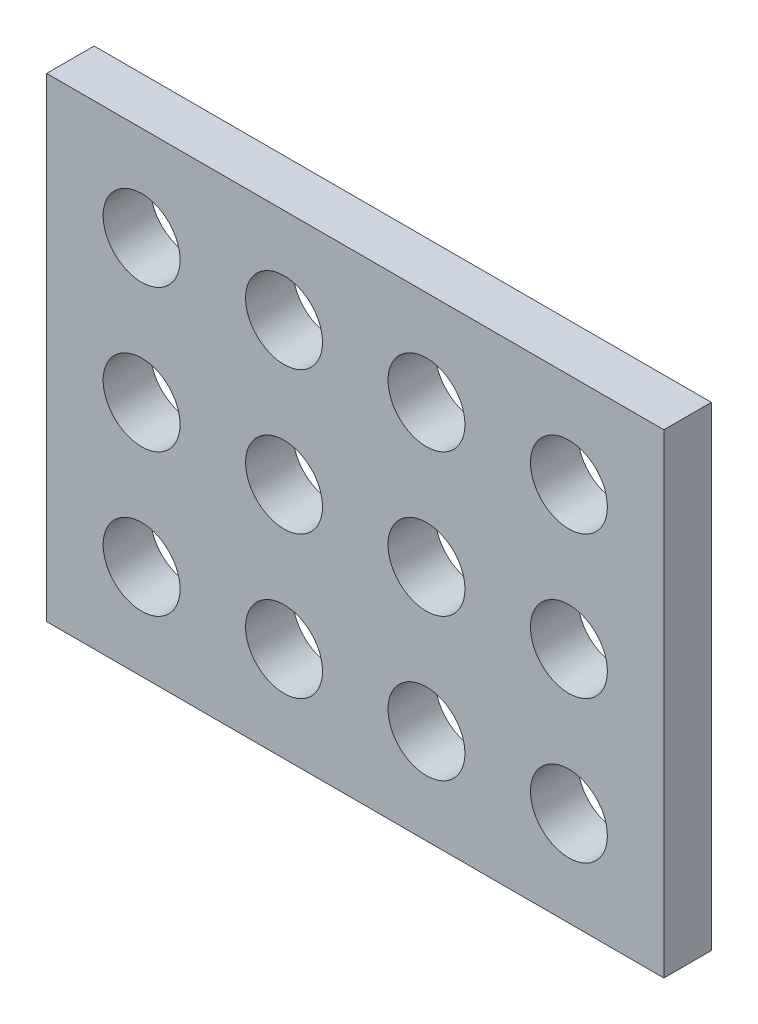
SolidWorks part; units mm, degrees
ref_plane "Alzado" through (0, 0, 0) normal (0, 0, 1) x (1, 0, 0)
ref_plane "Planta" through (0, 0, 0) normal (0, 1, 0) x (1, 0, 0)
ref_plane "Vista lateral" through (0, 0, 0) normal (1, 0, 0) x (0, 0, -1)
sketch "Croquis1" plane through (0, 0, 0) normal (0, 0, 1) x (1, 0, 0)
  line L0 (-100, 60) -> (-45, 60) construction
  line L1 (-65, -50) -> (65, -50)
  line L2 (-65, -50) -> (-65, 50)
  line L3 (-65, 50) -> (65, 50)
  line L4 (65, -50) -> (65, 50)
  line L5 (-65, -50) -> (65, 50) construction
  line L6 (-65, 50) -> (65, -50) construction
  line L7 (-45, 60) -> (-45, 30) construction
  line L8 (-45, 30) -> (-65, 30) construction
  circle A0 centre (-45, 30) radius 8.1
  circle A1 centre (-15, 30) radius 8.1
  circle A2 centre (15, 30) radius 8.1
  circle A3 centre (45, 30) radius 8.1
  circle A4 centre (-15, 0) radius 8.1
  circle A5 centre (15, 0) radius 8.1
  circle A6 centre (45, 0) radius 8.1
  circle A7 centre (-15, -30) radius 8.1
  circle A8 centre (15, -30) radius 8.1
  circle A9 centre (45, -30) radius 8.1
  circle A10 centre (-45, 0) radius 8.1
  circle A11 centre (-45, -30) radius 8.1
  point P0 (0, 0)
  dimension "D6" = 4
  dimension "D2" = 20
  dimension "D1" = 20
  dimension "D10" = 30
  dimension "D11" = 30
  dimension "D3" = 20
  dimension "D4" = 10
  dimension "D5" = 20
  dimension "D8" = 130
  dimension "D9" = 100
  dimension "D7" = 3
extrude "Saliente-Extruir1" add sketch "Croquis1" along normal blind 10
